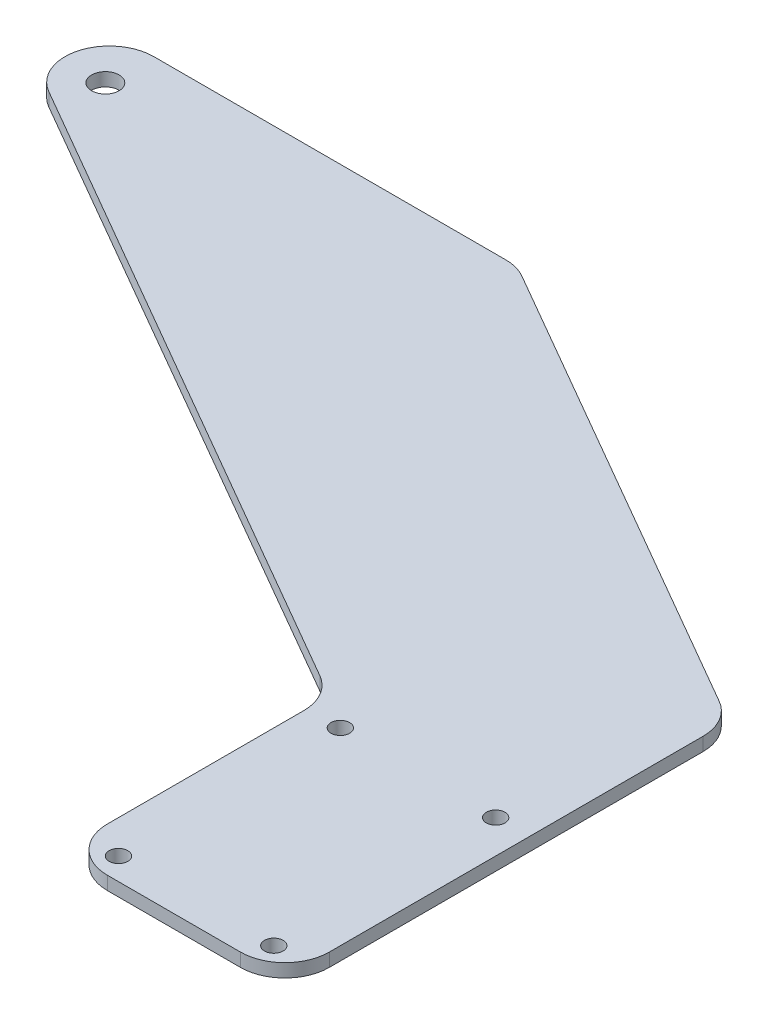
SolidWorks part; units mm, degrees
material "Thornel Mat VMA"
ref_plane "前视基准面" through (0, 0, 0) normal (0, 0, 1) x (1, 0, 0)
ref_plane "上视基准面" through (0, 0, 0) normal (0, 1, 0) x (1, 0, 0)
ref_plane "右视基准面" through (0, 0, 0) normal (1, 0, 0) x (0, 0, -1)
sketch "草图1" plane through (0, 0, 0) normal (0, 1, 0) x (1, 0, 0)
  line L0 (-7.5, 95) -> (-37.8109, 112.5) construction
  line L1 (0, 0) -> (35, 0) construction
  line L2 (0, 0) -> (0, 50) construction
  line L3 (0, 50) -> (35, 50) construction
  line L4 (35, 0) -> (35, 50) construction
  line L5 (17.5, 50) -> (17.5, 0) construction
  line L6 (0, 25) -> (35, 25) construction
  line L7 (-7.5, -5) -> (42.5, -5)
  line L8 (-7.5, -5) -> (-7.5, 55)
  line L9 (-7.5, 55) -> (42.5, 55) construction
  line L10 (42.5, -5) -> (42.5, 55)
  line L11 (-7.5, -5) -> (42.5, 55) construction
  line L12 (-7.5, 55) -> (42.5, -5) construction
  line L13 (-7.5, 55) -> (42.5, 55) construction
  line L15 (-7.5, 95) -> (42.5, 95) construction
  line L16 (42.5, 55) -> (42.5, 95)
  line L17 (17.5, 95) -> (17.5, 55) construction
  line L18 (-7.5, 75) -> (42.5, 75) construction
  line L19 (-7.5, 95) -> (42.5, 95) construction
  line L20 (-37.8109, 112.5) -> (12.1891, 112.5) construction
  line L21 (42.5, 95) -> (12.1891, 112.5)
  line L22 (-18.1218, 130) -> (-70.0833, 160)
  line L24 (-154.7243, 160) -> (-70.0833, 160)
  line L25 (12.1891, 112.5) -> (-18.1218, 130)
  line L26 (-7.5, 55) -> (-189.3653, 160)
  line L27 (-189.3653, 160) -> (-154.7243, 160)
  circle A0 centre (0, 50) radius 2.1
  circle A1 centre (35, 50) radius 2.1
  circle A2 centre (35, 0) radius 2.1
  circle A3 centre (0, 0) radius 2.1
  point P8 (17.5, 25)
  point P319 (17.5, 75)
  point P452 (17.5, 25)
  dimension "D3" = 4.2
  dimension "D9" = 130
  dimension "D1" = 50
  dimension "D2" = 35
  dimension "D4" = 60
  dimension "D5" = 50
  dimension "D6" = 40
  dimension "D7" = 30
  dimension "D8" = 70
extrude "凸台-拉伸1" add sketch "草图1" along normal blind 3
fillet "圆角1" radius 10 4 edges at (-7.5, 1.5, -55) (-70.0833, 1.5, -160) (-189.3653, 1.5, -160) (42.5, 1.5, -95)
sketch "草图2" plane through (0, 3, 0) normal (0, 1, 0) x (1, 0, 0)
  line L1 (-152.0448, 160) -> (42.5, 47.6795) construction
  line L2 (42.5, -5) -> (42.5, 89.2265) construction
  line L3 (-12.5, 57.8868) -> (-157.0448, 141.3397) construction
  line L4 (-157.0448, 141.3397) -> (-147.7147, 157.5) construction
  circle A0 centre (-152.3798, 149.4199) radius 3.1
  dimension "D3" = 6.2
extrude "切除-拉伸1" cut sketch "草图2" against normal blind 10
fillet "圆角2" radius 10 2 edges at (42.5, 1.5, 5) (-7.5, 1.5, 5)
